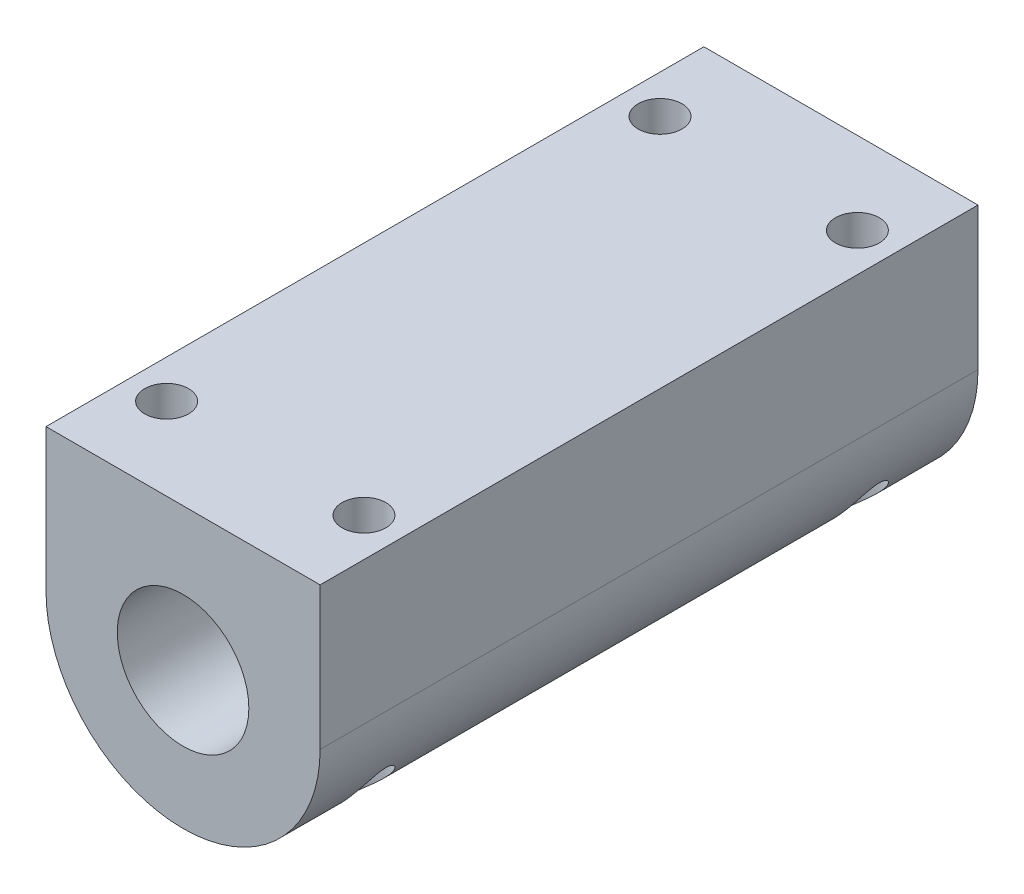
SolidWorks part; units mm, degrees
ref_plane "Plano frontal" through (0, 0, 0) normal (0, 0, 1) x (1, 0, 0)
ref_plane "Plano superior" through (0, 0, 0) normal (0, 1, 0) x (1, 0, 0)
ref_plane "Plano direito" through (0, 0, 0) normal (1, 0, 0) x (0, 0, -1)
sketch "Esboço1" plane through (0, 0, 0) normal (0, 0, 1) x (1, 0, 0)
  line L0 (-12.5, 0) -> (-12.5, 13)
  line L1 (-12.5, 13) -> (12.5, 13)
  line L2 (12.5, 13) -> (12.5, 0)
  arc A0 (-12.5, 0) -> (12.5, 0) centre (0, 0) ccw
  circle A1 centre (0, 0) radius 6
  dimension "D1" = 25
  dimension "D3" = 12
  dimension "D2" = 13
extrude "Ressalto-extrusão1" add sketch "Esboço1" along normal blind 60
sketch "Esboço3" plane through (0, 13, 0) normal (0, 1, 0) x (1, 0, 0)
  line L0 (0, -60) -> (0, 0) construction
  line L1 (12.5, -60) -> (-12.5, -60) construction
  line L2 (12.5, 0) -> (-12.5, 0) construction
  line L3 (-12.5, -30) -> (12.5, -30) construction
  line L4 (-12.5, -60) -> (-12.5, 0) construction
  line L5 (12.5, -60) -> (12.5, 0) construction
  circle A0 centre (-9, -52.5) radius 2
  circle A1 centre (-9, -7.5) radius 2
  circle A2 centre (9, -52.5) radius 2
  circle A3 centre (9, -7.5) radius 2
  dimension "D1" = 4
  dimension "D2" = 18
  dimension "D3" = 45
extrude "Corte-extrusão1" cut sketch "Esboço3" against normal through all
